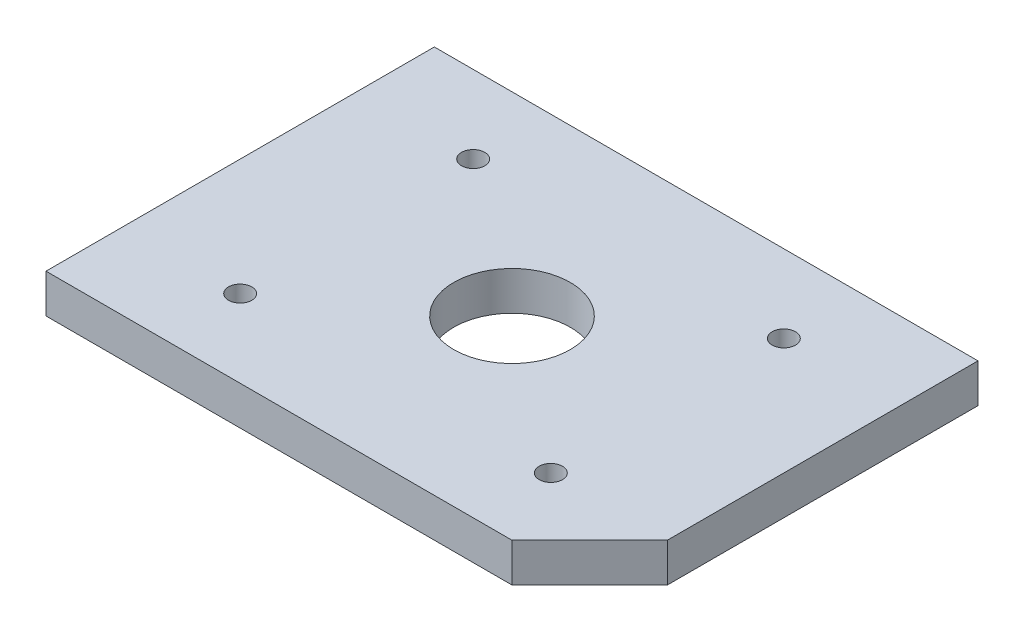
SolidWorks part; units mm, degrees
material "6061 Alloy"
ref_plane "Front Plane" through (0, 0, 0) normal (0, 0, 1) x (1, 0, 0)
ref_plane "Top Plane" through (0, 0, 0) normal (0, 1, 0) x (1, 0, 0)
ref_plane "Right Plane" through (0, 0, 0) normal (1, 0, 0) x (0, 0, -1)
sketch "Sketch1" plane through (0, 0, 0) normal (0, 1, 0) x (1, 0, 0)
  line L0 (25, -25) -> (35, -15)
  line L1 (-35, -25) -> (35, -25)
  line L2 (-35, -25) -> (-35, 25)
  line L3 (-35, 25) -> (35, 25)
  line L4 (35, -25) -> (35, 25)
  line L5 (-35, -25) -> (35, 25) construction
  line L6 (-35, 25) -> (35, -25) construction
  line L8 (-20, -15) -> (20, -15) construction
  line L9 (-20, -15) -> (-20, 15) construction
  line L10 (-20, 15) -> (20, 15) construction
  line L11 (20, -15) -> (20, 15) construction
  line L12 (-20, -15) -> (20, 15) construction
  line L13 (-20, 15) -> (20, -15) construction
  circle A0 centre (0, 0) radius 7.5
  circle A1 centre (-20, 15) radius 1.5
  circle A2 centre (20, 15) radius 1.5
  circle A3 centre (20, -15) radius 1.5
  circle A4 centre (-20, -15) radius 1.5
  point P0 (0, 0)
  point P18 (24.5127, 17.5091)
  point P19 (20, -14.2857)
  point P20 (20, -14.2857)
  point P21 (0, 0)
  point P22 (20, 17.9239)
  dimension "D3" = 15
  dimension "D4" = 3
  dimension "D1" = 50
  dimension "D2" = 70
  dimension "D5" = 40
  dimension "D6" = 30
  dimension "D7" = 10
  dimension "D8" = 10
extrude "Boss-Extrude1" add sketch "Sketch1" along normal blind 5 contours L0 L4 L3 L2 L1 A4 A3 A2 A1 A0
sketch "Sketch2" plane through (0, 5, 0) normal (0, 1, 0) x (1, 0, 0)
  line L6 (25, -25) -> (35, -15)
  line L7 (35, -15) -> (35, 25)
  line L8 (35, 25) -> (-35, 25)
  line L9 (-35, 25) -> (-35, -25)
  line L10 (-35, -25) -> (25, -25)
  line L11 (25, -25) -> (35, -15)
  line L12 (35, -15) -> (35, 25)
  line L13 (35, 25) -> (-35, 25)
  line L14 (-35, 25) -> (-35, -25)
  line L15 (-35, -25) -> (25, -25)
  circle A1 centre (-20, -15) radius 1.5
  circle A2 centre (-20, -15) radius 1.5
  circle A3 centre (20, -15) radius 1.5
  circle A4 centre (20, -15) radius 1.5
  circle A5 centre (20, 15) radius 1.5
  circle A6 centre (20, 15) radius 1.5
  circle A7 centre (-20, 15) radius 1.5
  circle A8 centre (-20, 15) radius 1.5
  circle A9 centre (0, 0) radius 7.5
  circle A10 centre (0, 0) radius 7.5
  dimension "D11" = 15
  dimension "D12" = 3
  dimension "D6" = 0
  dimension "D7" = 70
  dimension "D8" = 50
  dimension "D9" = 10
  dimension "D10" = 10
  dimension "D13" = 30
  dimension "D14" = 40
  dimension "D15" = 15
  dimension "D16" = 10
  dimension "D1" = 0
  dimension "D2" = 0
  dimension "D3" = 0
  dimension "D4" = 0
  dimension "D5" = 0
